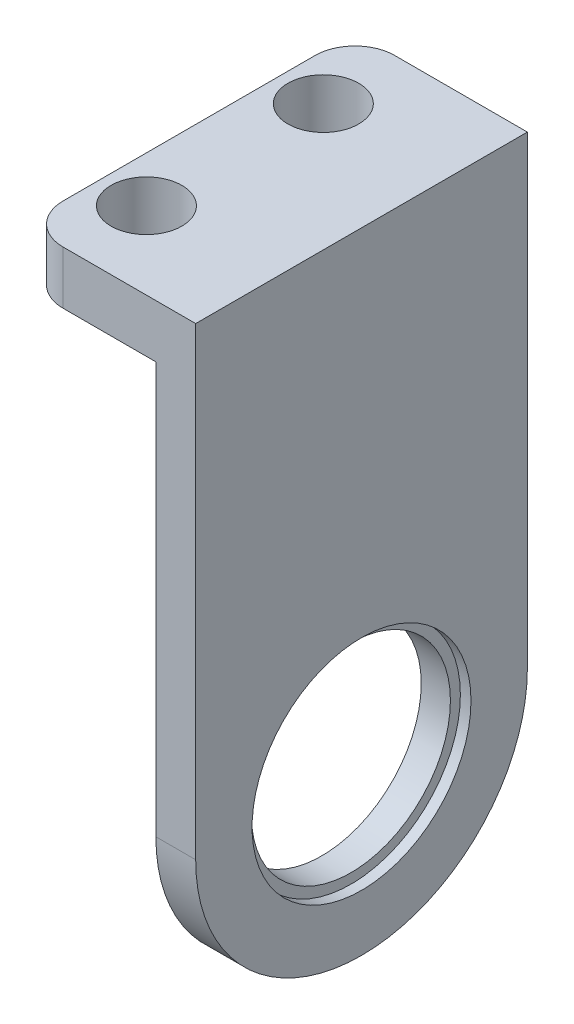
SolidWorks part; units mm, degrees
material "7075-O (SS)"
ref_plane "前视基准面" through (0, 0, 0) normal (0, 0, 1) x (1, 0, 0)
ref_plane "上视基准面" through (0, 0, 0) normal (0, 1, 0) x (1, 0, 0)
ref_plane "右视基准面" through (0, 0, 0) normal (1, 0, 0) x (0, 0, -1)
sketch "草图1" plane through (0, 0, 0) normal (1, 0, 0) x (0, 0, -1)
  line L2 (-12.5, 0) -> (-12.5, 35)
  line L3 (-12.5, 35) -> (12.5, 35)
  line L4 (12.5, 0) -> (12.5, 35)
  arc A0 (-12.5, 0) -> (12.5, 0) centre (0, 0) ccw
  circle A1 centre (0, 0) radius 7.5
  point P0 (-2.5, 12)
  dimension "D2" = 25
extrude "凸台-拉伸1" add sketch "草图1" along normal blind 3
sketch "草图2" plane through (0, 0, 0) normal (-1, 0, 0) x (0, 0, 1)
  line L0 (12.5, 35) -> (12.5, 0) construction
  line L1 (12.5, 31) -> (-12.5, 31)
  line L2 (12.5, 31) -> (12.5, 35)
  line L3 (12.5, 35) -> (-12.5, 35)
  line L4 (-12.5, 31) -> (-12.5, 35)
  dimension "D1" = 4
extrude "凸台-拉伸2" add sketch "草图2" along normal blind 10
fillet "圆角1" radius 3 2 edges at (-10, 33, 12.5) (-10, 33, -12.5)
ref_plane "基准面1" through (3, 0, 0) normal (1, 0, 0) x (0, 0, -1)
sketch "草图8" plane through (3, 0, 0) normal (1, 0, 0) x (0, 0, -1)
  circle A0 centre (0, 0) radius 8.25
extrude "切除-拉伸2" cut sketch "草图8" against normal blind 0.8
sketch "草图4" plane through (0, 35, 0) normal (0, 1, 0) x (1, 0, 0)
  line L0 (-10, 0) -> (3, 0)
  line L1 (-10, -9.5) -> (-10, 9.5) construction
  line L2 (3, 12.5) -> (3, -12.5) construction
  line L3 (-3.5, -9) -> (-3.5, 9)
  line L4 (-6.1645, -9) -> (-0.8355, -9)
  line L5 (-6.1645, -9) -> (-6.1645, 9)
  line L6 (-6.1645, 9) -> (-0.8355, 9)
  line L7 (-0.8355, -9) -> (-0.8355, 9)
  line L8 (-6.1645, -9) -> (-0.8355, 9) construction
  line L9 (-6.1645, 9) -> (-0.8355, -9) construction
  point P6 (-3.5, 0)
  dimension "D1" = 18
hole_wizard "M3 螺纹孔1" [suppressed] positions "草图6" profile "草图5" tap size "M3" standard "GB"
sketch "草图6" plane through (0, 15, 0) normal (0, 1, 0) x (1, 0, 0)
  point P0 (-3.5, 9)
  point P3 (-3.5, -9)
sketch "草图5" plane through (-3.5, 15, -9) normal (1, 0, 0) x (0, 0, 1)
  line L0 (0, 0) -> (0, 9.2511)
  line L1 (0, 9.2511) -> (1.25, 8.5)
  line L2 (1.25, 8.5) -> (1.25, 0)
  line L5 (1.25, 0) -> (0, 0)
  line L10 (0, 9.2511) -> (-1.25, 8.5) construction
  line L11 (0, -6.35) -> (0, 107.95) construction
  dimension "螺纹孔钻头直径" = 2.5
  dimension "螺纹孔钻头深度" = 8.5
  dimension "导头角度" = 118
chamfer "倒角1" [suppressed] distance 0.5 angle 45
scale "缩放比例1" scale about centroid uniform scaling yes scale factor 0.6
sketch "草图3" plane through (0, 28.8733, 0) normal (0, 1, 0) x (1, 0, 0)
  circle A0 centre (-4, 4) radius 1.6
  circle A1 centre (-4, -4) radius 1.6
  point P8 (-1.5138, 8)
  point P9 (-1.5138, -8)
extrude "切除-拉伸3" cut sketch "草图3" against normal blind 5
